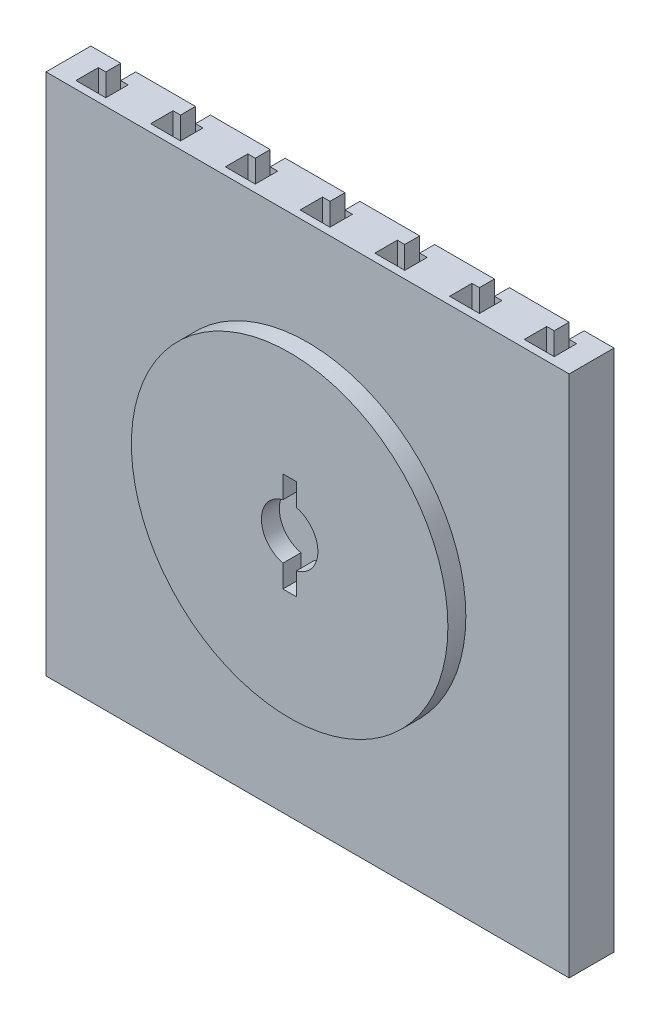
SolidWorks part; units mm, degrees
material "AISI 347 Annealed Stainless Steel (SS)"
ref_plane "Front Plane" through (0, 0, 0) normal (0, 0, 1) x (1, 0, 0)
ref_plane "Top Plane" through (0, 0, 0) normal (0, 1, 0) x (1, 0, 0)
ref_plane "Right Plane" through (0, 0, 0) normal (1, 0, 0) x (0, 0, -1)
sketch "Sketch1" plane through (0, 0, 0) normal (0, 0, 1) x (1, 0, 0)
  line L1 (-175, 175) -> (175, 175)
  line L2 (-175, 175) -> (-175, -175)
  line L3 (-175, -175) -> (175, -175)
  line L4 (175, 175) -> (175, -175)
  line L5 (-175, 175) -> (175, -175) construction
  line L6 (-175, -175) -> (175, 175) construction
  point P0 (0, 0)
  dimension "D1" = 350
  dimension "D2" = 350
extrude "Boss-Extrude1" add sketch "Sketch1" along normal blind 30
sketch "Sketch2" plane through (0, 0, 30) normal (0, 0, 1) x (1, 0, 0)
  line L5 (-76.73, 72.95) -> (76.73, -72.95) construction
  line L6 (-76.73, -72.95) -> (76.73, 72.95) construction
  circle A0 centre (0, 0) radius 105.8735
  point P0 (0, 0)
  dimension "D1" = 145.9
  dimension "D2" = 153.46
extrude "Boss-Extrude2" add sketch "Sketch2" along normal blind 12
sketch "Sketch3" plane through (0, 0, 42) normal (0, 0, 1) x (1, 0, 0)
  line L0 (-4.5, 18.3565) -> (-4.5, 33.3565)
  line L1 (-4.5, 33.3565) -> (4.5, 33.3565)
  line L2 (4.5, 33.3565) -> (4.5, 18.3565)
  line L3 (0, 9.0796) -> (0, -8.8737) construction
  line L4 (-10.8698, 0) -> (16.6105, 0) construction
  line L5 (4.5, -33.3565) -> (4.5, -18.3565)
  line L6 (-4.5, -33.3565) -> (4.5, -33.3565)
  line L7 (-4.5, -18.3565) -> (-4.5, -33.3565)
  arc A0 (-4.5, 18.3565) -> (-4.5, -18.3565) centre (0, 0) ccw
  arc A1 (4.5, -18.3565) -> (4.5, 18.3565) centre (0, 0) ccw
  point P9 (0, 33.3565)
  dimension "D1" = 37.8
  dimension "D2" = 15
  dimension "D3" = 9
extrude "Cut-Extrude1" cut sketch "Sketch3" against normal blind 12
sketch "Sketch5" plane through (0, 175, 0) normal (0, 1, 0) x (1, 0, 0)
  line L0 (-155, 0) -> (-155, -10)
  line L1 (175, 0) -> (-175, 0) construction
  line L2 (-155, -10) -> (-160, -10)
  line L3 (-160, -10) -> (-160, -25)
  line L4 (-160, -25) -> (-140, -25)
  line L5 (-140, -25) -> (-140, -10)
  line L6 (-140, -10) -> (-145, -10)
  line L7 (-145, -10) -> (-145, 0)
  line L8 (175, -30) -> (-175, -30) construction
  line L9 (-175, -30) -> (-175, 0) construction
  line L10 (-155, 0) -> (-145, 0)
  line L11 (-105, 0) -> (-105, -10)
  line L12 (-105, 0) -> (-95, 0)
  line L13 (-95, -10) -> (-95, 0)
  line L14 (-90, -10) -> (-95, -10)
  line L15 (-90, -25) -> (-90, -10)
  line L16 (-110, -10) -> (-110, -25)
  line L17 (-110, -25) -> (-90, -25)
  line L18 (-55, 0) -> (-55, -10)
  line L19 (-55, 0) -> (-45, 0)
  line L20 (-45, -10) -> (-45, 0)
  line L21 (-40, -10) -> (-45, -10)
  line L22 (-40, -25) -> (-40, -10)
  line L23 (-60, -10) -> (-60, -25)
  line L24 (-60, -25) -> (-40, -25)
  line L25 (-5, 0) -> (-5, -10)
  line L26 (-5, 0) -> (5, 0)
  line L27 (5, -10) -> (5, 0)
  line L28 (10, -10) -> (5, -10)
  line L29 (10, -25) -> (10, -10)
  line L30 (-10, -10) -> (-10, -25)
  line L31 (-10, -25) -> (10, -25)
  line L53 (-105, -10) -> (-110, -10)
  line L54 (-55, -10) -> (-60, -10)
  line L55 (-5, -10) -> (-10, -10)
  line L60 (45, 0) -> (45, -10) [skipped]
  line L61 (45, 0) -> (55, 0) [skipped]
  line L62 (55, -10) -> (55, 0) [skipped]
  line L63 (60, -10) -> (55, -10) [skipped]
  line L64 (60, -25) -> (60, -10) [skipped]
  line L65 (40, -10) -> (40, -25) [skipped]
  line L66 (40, -25) -> (60, -25) [skipped]
  line L67 (95, 0) -> (95, -10) [skipped]
  line L68 (95, 0) -> (105, 0) [skipped]
  line L69 (105, -10) -> (105, 0) [skipped]
  line L70 (110, -10) -> (105, -10) [skipped]
  line L71 (110, -25) -> (110, -10) [skipped]
  line L72 (90, -10) -> (90, -25) [skipped]
  line L73 (90, -25) -> (110, -25) [skipped]
  line L74 (145, 0) -> (145, -10) [skipped]
  line L75 (145, 0) -> (155, 0) [skipped]
  line L76 (155, -10) -> (155, 0) [skipped]
  line L77 (160, -10) -> (155, -10) [skipped]
  line L78 (160, -25) -> (160, -10) [skipped]
  line L79 (140, -10) -> (140, -25) [skipped]
  line L80 (140, -25) -> (160, -25) [skipped]
  line L81 (45, -10) -> (40, -10) [skipped]
  line L82 (95, -10) -> (90, -10) [skipped]
  line L83 (5, -10) -> (10, -10)
  line L84 (55, -10) -> (60, -10)
  line L85 (105, -10) -> (110, -10)
  line L86 (10, -25) -> (-10, -25)
  line L87 (10, -10) -> (10, -25)
  line L88 (-10, -25) -> (-10, -10)
  line L89 (-10, -10) -> (-5, -10)
  line L90 (-5, -10) -> (-5, 0)
  line L91 (5, 0) -> (-5, 0)
  line L92 (5, 0) -> (5, -10)
  line L93 (60, -25) -> (40, -25)
  line L94 (60, -10) -> (60, -25)
  line L95 (40, -25) -> (40, -10)
  line L96 (40, -10) -> (45, -10)
  line L97 (45, -10) -> (45, 0)
  line L98 (55, 0) -> (45, 0)
  line L99 (55, 0) -> (55, -10)
  line L100 (110, -25) -> (90, -25)
  line L101 (110, -10) -> (110, -25)
  line L102 (90, -25) -> (90, -10)
  line L103 (90, -10) -> (95, -10)
  line L104 (95, -10) -> (95, 0)
  line L105 (105, 0) -> (95, 0)
  line L106 (105, 0) -> (105, -10)
  line L107 (155, 0) -> (145, 0)
  line L108 (145, -10) -> (145, 0)
  line L109 (140, -10) -> (145, -10)
  line L110 (140, -25) -> (140, -10)
  line L111 (160, -25) -> (140, -25)
  line L112 (160, -10) -> (160, -25)
  line L113 (155, -10) -> (160, -10)
  line L114 (155, 0) -> (155, -10)
  point P4 (-145, -5)
  line M1 (175, 0) -> (-175, 0)
  dimension "D1" = 20
  dimension "D2" = 10
  dimension "D3" = 5
  dimension "D4" = 10
  dimension "D5" = 15
  dimension "D6" = 7
  dimension "D7" = 6
extrude "Cut-Extrude3" cut sketch "Sketch5" against normal through all contours L6 L7 L0 L2 L3 L4 L5 M1 | L11 L53 L16 L17 L15 L14 L13 M1 | L18 L54 L23 L24 L22 L21 L20 M1 | L25 L55 L30 L31 L29 L28 L27 M1 | L99 L97 L96 L95 L93 L94 L84 M1 | L106 L104 L103 L102 L100 L101 L85 M1 | L114 L108 L109 L110 L111 L112 L113 M1
